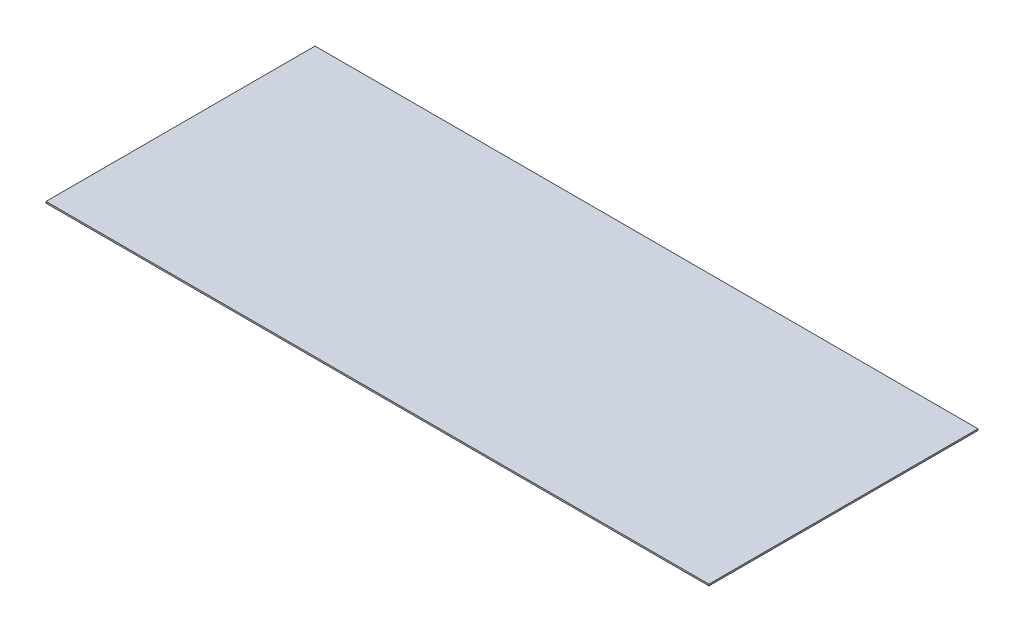
SolidWorks part; units mm, degrees
ref_plane "Front Plane" through (0, 0, 0) normal (0, 0, 1) x (1, 0, 0)
ref_plane "Top Plane" through (0, 0, 0) normal (0, 1, 0) x (1, 0, 0)
ref_plane "Right Plane" through (0, 0, 0) normal (1, 0, 0) x (0, 0, -1)
sketch "Sketch1" plane through (0, 0, 0) normal (0, 1, 0) x (1, 0, 0)
  line L1 (-673.354, -273.304) -> (673.354, -273.304)
  line L2 (-673.354, -273.304) -> (-673.354, 273.304)
  line L3 (-673.354, 273.304) -> (673.354, 273.304)
  line L4 (673.354, -273.304) -> (673.354, 273.304)
  line L5 (-673.354, -273.304) -> (673.354, 273.304) construction
  line L6 (-673.354, 273.304) -> (673.354, -273.304) construction
  point P0 (0, 0)
  dimension "D1" = 1346.708
  dimension "D2" = 546.608
extrude "Boss-Extrude1" add sketch "Sketch1" along normal blind 3.175
